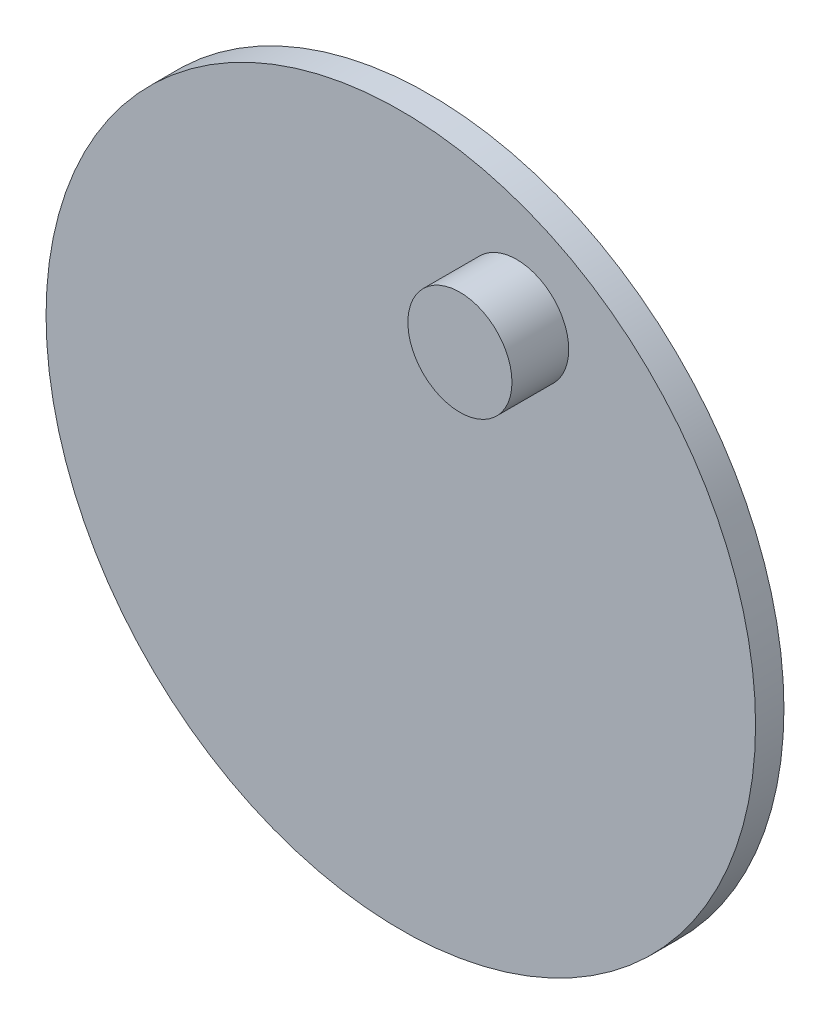
SolidWorks part; units mm, degrees
ref_plane "Front Plane" through (0, 0, 0) normal (0, 0, 1) x (1, 0, 0)
ref_plane "Top Plane" through (0, 0, 0) normal (0, 1, 0) x (1, 0, 0)
ref_plane "Right Plane" through (0, 0, 0) normal (1, 0, 0) x (0, 0, -1)
sketch "Sketch1" plane through (0, 0, 0) normal (0, 0, 1) x (1, 0, 0)
  circle A0 centre (0, 0) radius 75
  dimension "D1" = 150
extrude "Boss-Extrude3" add sketch "Sketch1" along normal blind 6
sketch "Sketch5" plane through (0, 0, 6) normal (0, 0, 1) x (1, 0, 0)
  circle A0 centre (24.4953, 48.9906) radius 11
  dimension "D1" = 22
extrude "Boss-Extrude4" add sketch "Sketch5" along normal blind 12
